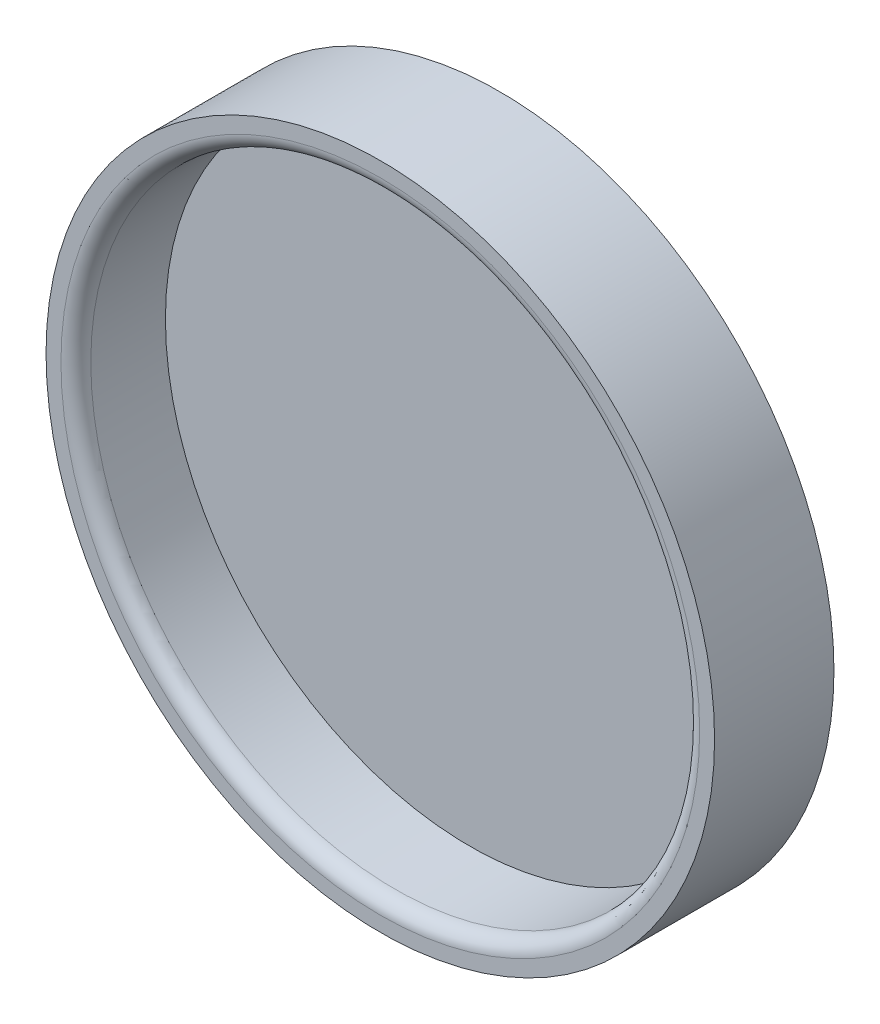
SolidWorks part; units mm, degrees
ref_plane "Front Plane" through (0, 0, 0) normal (0, 0, 1) x (1, 0, 0)
ref_plane "Top Plane" through (0, 0, 0) normal (0, 1, 0) x (1, 0, 0)
ref_plane "Right Plane" through (0, 0, 0) normal (1, 0, 0) x (0, 0, -1)
sketch "Sketch1" plane through (0, 0, 0) normal (0, 0, 1) x (1, 0, 0)
  circle A0 centre (0, 0) radius 11.2
  dimension "D1" = 22.4
extrude "Boss-Extrude1" add sketch "Sketch1" along normal blind 1
sketch "Sketch2" plane through (0, 0, 1) normal (0, 0, 1) x (1, 0, 0)
  circle A0 centre (0, 0) radius 11.2
  circle A1 centre (0, 0) radius 10.2
  circle A2 centre (0, 0) radius 11.2 construction
  dimension "D1" = 1
extrude "Boss-Extrude2" add sketch "Sketch2" along normal blind 3
fillet "Fillet1" radius 0.5 1 edges at (10.2, 0, 4)
